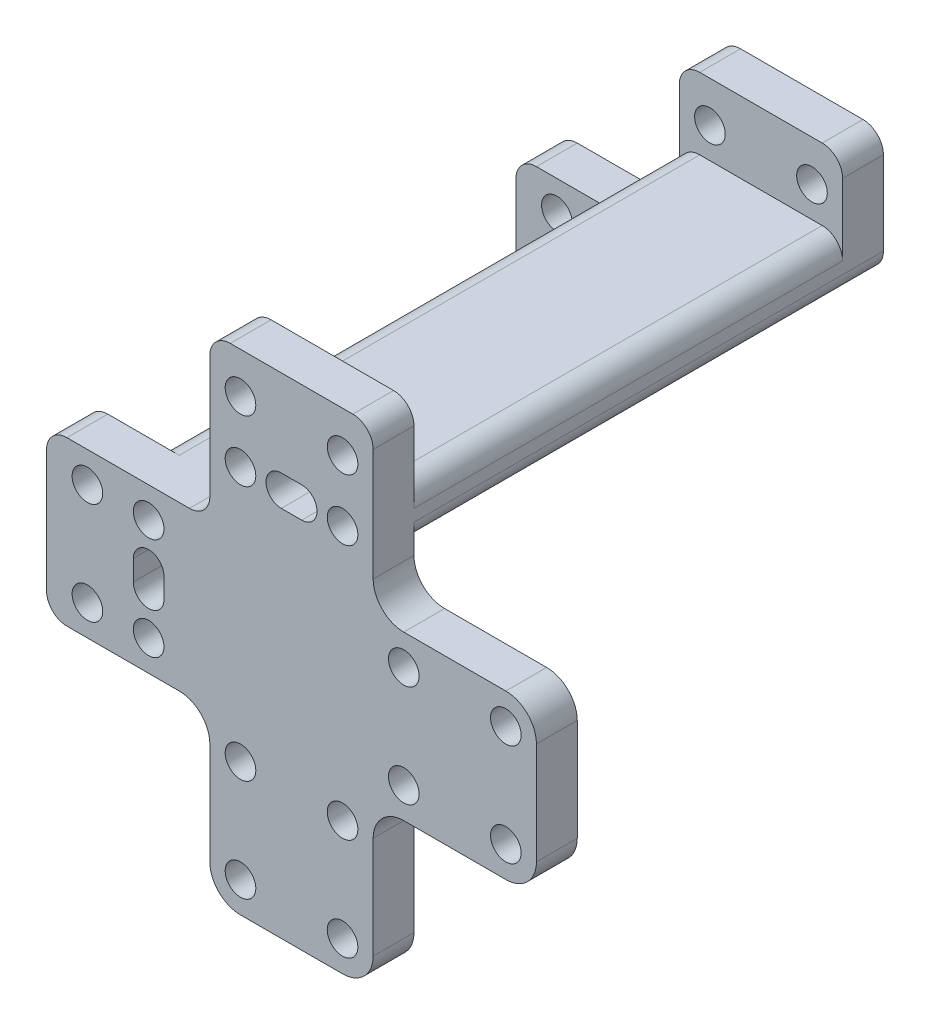
SolidWorks part; units mm, degrees
material "6061 合金"
ref_plane "前视基准面" through (0, 0, 0) normal (0, 0, 1) x (1, 0, 0)
ref_plane "上视基准面" through (0, 0, 0) normal (0, 1, 0) x (1, 0, 0)
ref_plane "右视基准面" through (0, 0, 0) normal (1, 0, 0) x (0, 0, -1)
other "Configuration Table"
sketch "草图1" plane through (0, 0, 0) normal (0, 0, 1) x (1, 0, 0)
  line L0 (-13, -8) -> (8, 13)
  line L1 (-5, 5) -> (5, 5) construction
  line L2 (-5, 5) -> (-5, -5) construction
  line L3 (-5, -5) -> (5, -5) construction
  line L4 (5, 5) -> (5, -5) construction
  line L5 (-5, 5) -> (5, -5) construction
  line L6 (-5, -5) -> (5, 5) construction
  line L7 (-5, 20) -> (5, 20) construction
  line L8 (-5, 20) -> (-5, 5) construction
  line L9 (-5, 5) -> (5, 5) construction
  line L10 (5, 20) -> (5, 5) construction
  line L11 (-20, 5) -> (-5, 5) construction
  line L12 (-20, 5) -> (-20, -5) construction
  line L13 (-20, -5) -> (-5, -5) construction
  line L14 (-5, 5) -> (-5, -5) construction
  line L15 (-8, 24) -> (8, 24)
  line L16 (-8, 24) -> (-8, 1)
  line L17 (-8, 1) -> (8, 1)
  line L18 (8, 24) -> (8, 1)
  line L19 (-8, 24) -> (8, 1) construction
  line L20 (-8, 1) -> (8, 24) construction
  line L21 (-24, 8) -> (-1, 8)
  line L22 (-24, 8) -> (-24, -8)
  line L23 (-24, -8) -> (-1, -8)
  line L24 (-1, 8) -> (-1, -8)
  line L25 (-24, 8) -> (-1, -8) construction
  line L26 (-24, -8) -> (-1, 8) construction
  circle A0 centre (-5, 5) radius 1.5
  circle A1 centre (-20, 5) radius 1.5
  circle A2 centre (-20, -5) radius 1.5
  circle A3 centre (-5, -5) radius 1.5 construction
  circle A4 centre (5, 5) radius 1.5 construction
  circle A5 centre (5, 20) radius 1.5
  circle A6 centre (-5, 20) radius 1.5
  point P0 (0, 0)
  point P8 (0, 12.5)
  point P24 (-12.5, 0)
  dimension "D7" = 3
  dimension "D1" = 10
  dimension "D2" = 10
  dimension "D8" = 16
  dimension "D9" = 23
  dimension "D10" = 23
  dimension "D11" = 16
  dimension "D12" = 11
  dimension "D13" = 11
  dimension "D3" = 2
  dimension "D4" = 2
  dimension "D5" = 2
  dimension "D6" = 2
extrude "凸台-拉伸1" add sketch "草图1" along normal blind 4 contours L22 L23 L0 L17 L16 L21 A2 A1 | L21 L24 L0 L18 L15 L16 A6 A5 | L24 L21 L16 L17 L0 A0
sketch "草图2" plane through (0, 0, 4) normal (0, 0, 1) x (1, 0, 0)
  line L1 (-8, 17) -> (8, 17)
  line L2 (-8, 24) -> (-8, 8) construction
  line L4 (8, 24) -> (8, 13) construction
  line L5 (-17, 8) -> (-8, 8)
  line L11 (-17, 8) -> (-17, -8)
  line L12 (-24, 8) -> (-8, 8) construction
  line L13 (-24, -8) -> (-13, -8) construction
  line L14 (-8, 8) -> (-8, 17)
  line L15 (8, 17) -> (8, 13)
  line L16 (8, 13) -> (-13, -8)
  line L17 (-13, -8) -> (-17, -8)
  circle A0 centre (-20, 5) radius 1.5 construction
  circle A1 centre (5, 20) radius 1.5 construction
  circle A2 centre (-5, 5) radius 1.5
  dimension "D1" = 3
  dimension "D2" = 3
extrude "凸台-拉伸2" add sketch "草图2" along normal blind 16
sketch "草图4" plane through (0, 0, 0) normal (0, 0, -1) x (-1, 0, 0)
  line L7 (-2.1716, 10) -> (6, 10)
  line L8 (10.2772, 6) -> (10.2772, -2.4488)
  line L9 (15, 6) -> (15, -6)
  line L10 (-6, 15) -> (6, 15)
  line L11 (10.2772, -2.4488) -> (13.8284, -6)
  line L14 (-6, 13.8284) -> (13.8284, -6)
  line L15 (13.8284, -6) -> (22, -6)
  line L16 (22, -6) -> (22, 6)
  line L17 (22, 6) -> (6, 6)
  line L18 (6, 6) -> (6, 22)
  line L19 (6, 22) -> (-6, 22)
  line L20 (-6, 22) -> (-6, 13.8284)
  line L21 (-6, 13.8284) -> (-2.1716, 10)
  line L22 (13.8284, -6) -> (15, -6)
  line L24 (15, 6) -> (10.2772, 6)
  line L25 (6, 10) -> (6, 15)
  line L27 (-6, 15) -> (-6, 13.8284)
  circle A0 centre (5, 5) radius 1.5 construction
  circle A1 centre (-5, 20) radius 1.5 construction
  circle A2 centre (20, 5) radius 1.5 construction
  dimension "D2" = 5
  dimension "D3" = 5.2772
  dimension "D4" = 5
  dimension "D5" = 5
  dimension "D1" = 2
extrude "切除-拉伸4" cut sketch "草图4" against normal blind 10
sketch "草图5" plane through (0, 0, 20) normal (0, 0, 1) x (1, 0, 0)
  circle A0 centre (-14, 5) radius 1.25
  circle A1 centre (-14, -5) radius 1.25
  circle A2 centre (-5, 14) radius 1.25
  circle A3 centre (5, 14) radius 1.25
  circle A4 centre (-5, 20) radius 1.5 construction
  circle A5 centre (-20, 5) radius 1.5 construction
  circle A6 centre (-20, -5) radius 1.5 construction
  circle A7 centre (5, 20) radius 1.5 construction
  dimension "D1" = 2.5
  dimension "D2" = 6
  dimension "D3" = 10
  dimension "D4" = 10
  dimension "D5" = 6
  dimension "D6" = 6
  dimension "D7" = 6
extrude "切除-拉伸5" cut sketch "草图5" against normal blind 8
sketch "草图6" plane through (0, 0, 20) normal (0, 0, 1) x (1, 0, 0)
  line L0 (-17, 8) -> (-8, 8)
  line L1 (-8, 8) -> (-8, 17)
  line L2 (-8, 17) -> (8, 17)
  line L3 (8, 17) -> (8, 13)
  line L4 (8, 13) -> (-13, -8)
  line L5 (-13, -8) -> (-17, -8)
  line L6 (-17, -8) -> (-17, 8)
  circle A0 centre (-14, 5) radius 1.5
  circle A1 centre (-14, -5) radius 1.5
  circle A2 centre (-5, 14) radius 1.5
  circle A3 centre (5, 14) radius 1.5
  dimension "D1" = 3
extrude "凸台-拉伸3" add sketch "草图6" along normal blind 30
sketch "草图7" plane through (0, 0, 50) normal (0, 0, 1) x (1, 0, 0)
  line L0 (-5, 14) -> (5, 14) construction
  line L1 (-14, 5) -> (-14, -5) construction
  line L2 (-1, 14) -> (1, 14) construction
  line L3 (-1, 15.5) -> (1, 15.5)
  line L4 (-1, 12.5) -> (1, 12.5)
  line L5 (-14, 1) -> (-14, -1) construction
  line L6 (-12.5, 1) -> (-12.5, -1)
  line L7 (-15.5, 1) -> (-15.5, -1)
  arc A0 (-1, 15.5) -> (-1, 12.5) centre (-1, 14) ccw
  arc A1 (1, 12.5) -> (1, 15.5) centre (1, 14) ccw
  arc A2 (-12.5, 1) -> (-15.5, 1) centre (-14, 1) ccw
  arc A3 (-15.5, -1) -> (-12.5, -1) centre (-14, -1) ccw
  point P10 (0, 14)
  point P17 (-14, 0)
  dimension "D3" = 1.5
  dimension "D6" = 1.5
  dimension "D1" = 4
  dimension "D2" = 4
  dimension "D4" = 4
  dimension "D5" = 4
extrude "切除-拉伸6" cut sketch "草图7" against normal blind 29
fillet "圆角2" radius 2 11 edges at (-13, -8, 25) (8, 13, 25) (-8, 24, 2) (8, 24, 2) (8, 17, 27) (-17, -8, 27) (-24, -8, 2) (-24, 8, 2) (-17, 8, 27) (-8, 17, 27) (-8, 8, 25)
sketch "草图11" plane through (0, 0, 50) normal (0, 0, 1) x (1, 0, 0)
  line L0 (0, 0) -> (-2.5, 2.5) construction
  line L1 (-13.8284, -8) -> (-8, -8)
  line L2 (8, 13.8284) -> (8, 8)
  line L4 (24, 8) -> (24, -8)
  line L5 (24, -8) -> (8, -8)
  line L6 (11, 5) -> (21, 5) construction
  line L7 (-8, -24) -> (8, -24)
  line L8 (8, -24) -> (8, -8)
  line L9 (-12.4142, -7.4142) -> (7.4142, 12.4142) construction
  line L10 (-12.4142, -7.4142) -> (7.4142, 12.4142)
  line L11 (-8, -8) -> (-8, -24)
  line L12 (11, 5) -> (11, -5) construction
  line L13 (8, 8) -> (24, 8)
  line L14 (11, -5) -> (21, -5) construction
  line L15 (21, 5) -> (21, -5) construction
  line L16 (11, 5) -> (21, -5) construction
  line L17 (11, -5) -> (21, 5) construction
  arc A1 (-13.8284, -8) -> (-12.4142, -7.4142) centre (-13.8284, -6) ccw construction
  arc A2 (7.4142, 12.4142) -> (8, 13.8284) centre (6, 13.8284) ccw construction
  arc A3 (-13.8284, -8) -> (-12.4142, -7.4142) centre (-13.8284, -6) ccw
  arc A4 (7.4142, 12.4142) -> (8, 13.8284) centre (6, 13.8284) ccw
  circle A5 centre (21, 5) radius 1.5
  circle A6 centre (21, -5) radius 1.5
  circle A7 centre (11, -5) radius 1.5
  circle A8 centre (11, 5) radius 1.5
  circle A10 centre (5, -21) radius 1.5
  circle A11 centre (-5, -21) radius 1.5
  circle A12 centre (-5, -11) radius 1.5
  circle A13 centre (5, -11) radius 1.5
  point P4 (16, 0)
  dimension "D5" = 10
  dimension "D7" = 3
  dimension "D8" = 3
  dimension "D9" = 3
  dimension "D10" = 3
  dimension "D1" = 16
  dimension "D2" = 16
  dimension "D3" = 16
  dimension "D4" = 16
  dimension "D6" = 10
extrude "凸台-拉伸4" add sketch "草图11" against normal blind 4
fillet "圆角3" radius 3 7 edges at (8, 8, 48) (24, 8, 48) (24, -8, 48) (8, -8, 48) (8, -24, 48) (-8, -24, 48) (-8, -8, 48)
sketch "草图13" plane through (0, 0, 50) normal (0, 0, 1) x (1, 0, 0)
  line L0 (6, 24) -> (-6, 24) construction
  line L1 (-8, 22) -> (-8, 15) construction
  line L2 (-6, 17) -> (6, 17) construction
  line L3 (8, 15) -> (8, 22) construction
  line L4 (-24, 6) -> (-24, -6) construction
  line L5 (-22, -8) -> (-15, -8) construction
  line L6 (-17, -6) -> (-17, 6) construction
  line L7 (-15, 8) -> (-22, 8) construction
  line L8 (6, 24) -> (-6, 24)
  line L9 (-8, 22) -> (-8, 15)
  line L10 (-6, 17) -> (6, 17)
  line L11 (8, 15) -> (8, 22)
  line L12 (24, -5) -> (24, 5)
  line L13 (21, 8) -> (11, 8)
  line L14 (8, 11) -> (8, 15)
  line L15 (6, 17) -> (-6, 17)
  line L16 (-8, 15) -> (-8, 10)
  line L17 (-10, 8) -> (-15, 8)
  line L18 (-17, 6) -> (-17, -6)
  line L19 (-15, -8) -> (-11, -8)
  line L20 (-8, -11) -> (-8, -21)
  line L21 (-5, -24) -> (5, -24)
  line L22 (8, -21) -> (8, -11)
  line L23 (11, -8) -> (21, -8)
  line L24 (24, -5) -> (24, 5)
  line L25 (21, 8) -> (11, 8)
  line L26 (8, 11) -> (8, 15)
  line L27 (6, 17) -> (-6, 17)
  line L28 (-8, 15) -> (-8, 10)
  line L29 (-10, 8) -> (-15, 8)
  line L30 (-17, 6) -> (-17, -6)
  line L31 (-15, -8) -> (-11, -8)
  line L32 (-8, -11) -> (-8, -21)
  line L33 (-5, -24) -> (5, -24)
  line L34 (8, -21) -> (8, -11)
  line L35 (11, -8) -> (21, -8)
  line L36 (-24, 6) -> (-24, -6)
  line L37 (-22, -8) -> (-15, -8)
  line L38 (-17, -6) -> (-17, 6)
  line L39 (-15, 8) -> (-22, 8)
  arc A0 (-6, 24) -> (-8, 22) centre (-6, 22) ccw construction
  arc A1 (-6, 17) -> (-8, 15) centre (-6, 15) ccw construction
  arc A2 (8, 15) -> (6, 17) centre (6, 15) ccw construction
  arc A3 (8, 22) -> (6, 24) centre (6, 22) ccw construction
  arc A4 (-24, -6) -> (-22, -8) centre (-22, -6) ccw construction
  arc A5 (-17, -6) -> (-15, -8) centre (-15, -6) ccw construction
  arc A6 (-15, 8) -> (-17, 6) centre (-15, 6) ccw construction
  arc A7 (-22, 8) -> (-24, 6) centre (-22, 6) ccw construction
  arc A8 (-6, 24) -> (-8, 22) centre (-6, 22) ccw
  arc A9 (-6, 17) -> (-8, 15) centre (-6, 15) ccw
  arc A10 (8, 15) -> (6, 17) centre (6, 15) ccw
  arc A11 (8, 22) -> (6, 24) centre (6, 22) ccw
  arc A12 (24, 5) -> (21, 8) centre (21, 5) ccw
  arc A13 (8, 11) -> (11, 8) centre (11, 11) ccw
  arc A14 (8, 15) -> (6, 17) centre (6, 15) ccw
  arc A15 (-6, 17) -> (-8, 15) centre (-6, 15) ccw
  arc A16 (-10, 8) -> (-8, 10) centre (-10, 10) ccw
  arc A17 (-15, 8) -> (-17, 6) centre (-15, 6) ccw
  arc A18 (-17, -6) -> (-15, -8) centre (-15, -6) ccw
  arc A19 (-8, -11) -> (-11, -8) centre (-11, -11) ccw
  arc A20 (-8, -21) -> (-5, -24) centre (-5, -21) ccw
  arc A21 (5, -24) -> (8, -21) centre (5, -21) ccw
  arc A22 (11, -8) -> (8, -11) centre (11, -11) ccw
  arc A23 (21, -8) -> (24, -5) centre (21, -5) ccw
  arc A24 (24, 5) -> (21, 8) centre (21, 5) ccw
  arc A25 (8, 11) -> (11, 8) centre (11, 11) ccw
  arc A26 (8, 15) -> (6, 17) centre (6, 15) ccw
  arc A27 (-6, 17) -> (-8, 15) centre (-6, 15) ccw
  arc A28 (-10, 8) -> (-8, 10) centre (-10, 10) ccw
  arc A29 (-15, 8) -> (-17, 6) centre (-15, 6) ccw
  arc A30 (-17, -6) -> (-15, -8) centre (-15, -6) ccw
  arc A31 (-8, -11) -> (-11, -8) centre (-11, -11) ccw
  arc A32 (-8, -21) -> (-5, -24) centre (-5, -21) ccw
  arc A33 (5, -24) -> (8, -21) centre (5, -21) ccw
  arc A34 (11, -8) -> (8, -11) centre (11, -11) ccw
  arc A35 (21, -8) -> (24, -5) centre (21, -5) ccw
  arc A36 (-24, -6) -> (-22, -8) centre (-22, -6) ccw
  arc A37 (-17, -6) -> (-15, -8) centre (-15, -6) ccw
  arc A38 (-15, 8) -> (-17, 6) centre (-15, 6) ccw
  arc A39 (-22, 8) -> (-24, 6) centre (-22, 6) ccw
  circle A40 centre (-5, 20) radius 1.5
  circle A41 centre (5, 20) radius 1.5
  circle A42 centre (-20, 5) radius 1.5
  circle A43 centre (-20, -5) radius 1.5
  arc M38 (8, 15) -> (6, 17) centre (6, 15) ccw
  line M39 (6, 17) -> (-6, 17)
  arc M40 (-6, 17) -> (-8, 15) centre (-6, 15) ccw
  arc M44 (-15, 8) -> (-17, 6) centre (-15, 6) ccw
  line M45 (-17, 6) -> (-17, -6)
  arc M46 (-17, -6) -> (-15, -8) centre (-15, -6) ccw
  dimension "D1" = 0
extrude "凸台-拉伸5" add sketch "草图13" against normal blind 4 contours L39 A39 L36 A36 L37 M46 M45 M44 | L11 A11 L8 A8 L9 M40 M39 M38
